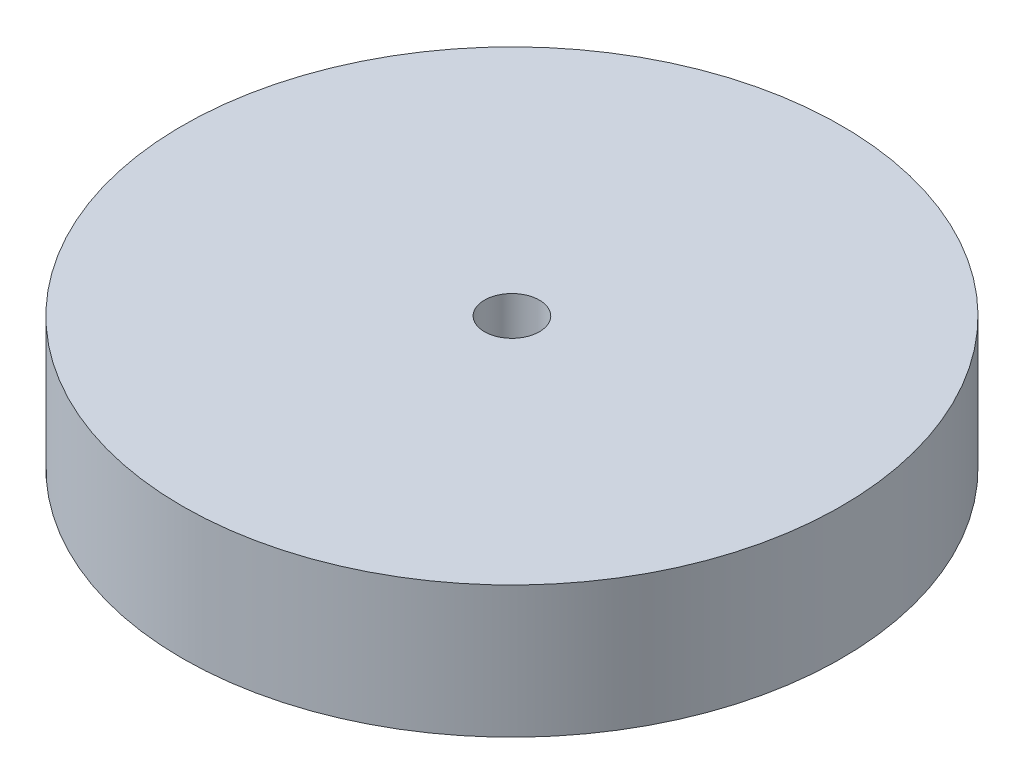
SolidWorks part; units mm, degrees
ref_plane "Front Plane" through (0, 0, 0) normal (0, 0, 1) x (1, 0, 0)
ref_plane "Top Plane" through (0, 0, 0) normal (0, 1, 0) x (1, 0, 0)
ref_plane "Right Plane" through (0, 0, 0) normal (1, 0, 0) x (0, 0, -1)
sketch "Sketch1" plane through (0, 0, 0) normal (0, 1, 0) x (1, 0, 0)
  circle A0 centre (0, 0) radius 30
  dimension "D1" = 60
extrude "Boss-Extrude1" add sketch "Sketch1" along normal blind 12
sketch "Sketch3" plane through (0, 12, 0) normal (0, 1, 0) x (1, 0, 0)
  circle A0 centre (0, 0) radius 2.5
  dimension "D1" = 5
extrude "Cut-Extrude3" cut sketch "Sketch3" against normal blind 6
sketch "Sketch4" plane through (0, 0, 0) normal (0, -1, 0) x (1, 0, 0)
  circle A0 centre (0, 0) radius 5
  dimension "D1" = 10
extrude "Cut-Extrude4" cut sketch "Sketch4" against normal blind 6
